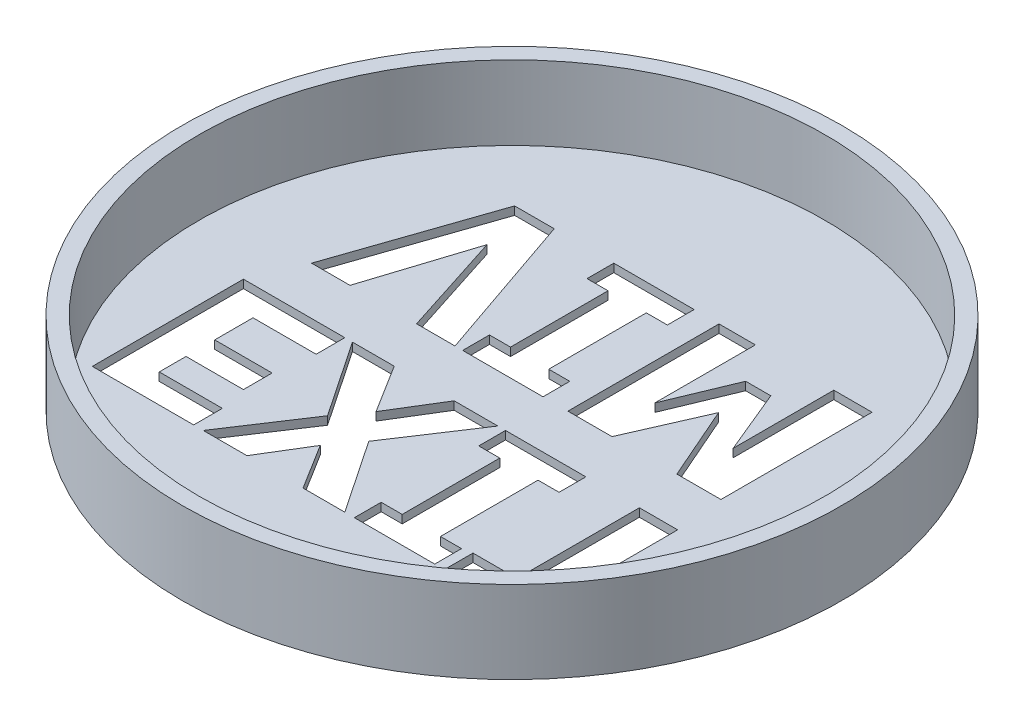
SolidWorks part; units mm, degrees
ref_plane "Front Plane" through (0, 0, 0) normal (0, 0, 1) x (1, 0, 0)
ref_plane "Top Plane" through (0, 0, 0) normal (0, 1, 0) x (1, 0, 0)
ref_plane "Right Plane" through (0, 0, 0) normal (1, 0, 0) x (0, 0, -1)
sketch "Sketch1" plane through (0, 0, 0) normal (0, 1, 0) x (1, 0, 0)
  circle A0 centre (0, 0) radius 40
  dimension "D1" = 80
extrude "Boss-Extrude1" add sketch "Sketch1" along normal blind 10
sketch "Sketch2" plane through (0, 10, 0) normal (0, 1, 0) x (1, 0, 0)
  circle A0 centre (0, 0) radius 38
  dimension "D1" = 76
extrude "Cut-Extrude1" cut sketch "Sketch2" against normal blind 9
sketch "Sketch3" [suppressed] plane through (0, 0, 0) normal (0, -1, 0) x (1, 0, 0)
  circle A0 centre (0, 0) radius 37 construction
  text T0 "EXIT VIM" font "Consolas" height in points 64
  dimension "D1" = 74
sketch "Sketch4" plane through (0, 0, 0) normal (0, -1, 0) x (1, 0, 0)
  text T0 "EXIT\r\n" font "Tahoma" height in points 68
  text T1 "VIM" font "Tahoma" height in points 68
extrude "Cut-Extrude2" cut sketch "Sketch4" against normal blind 8
